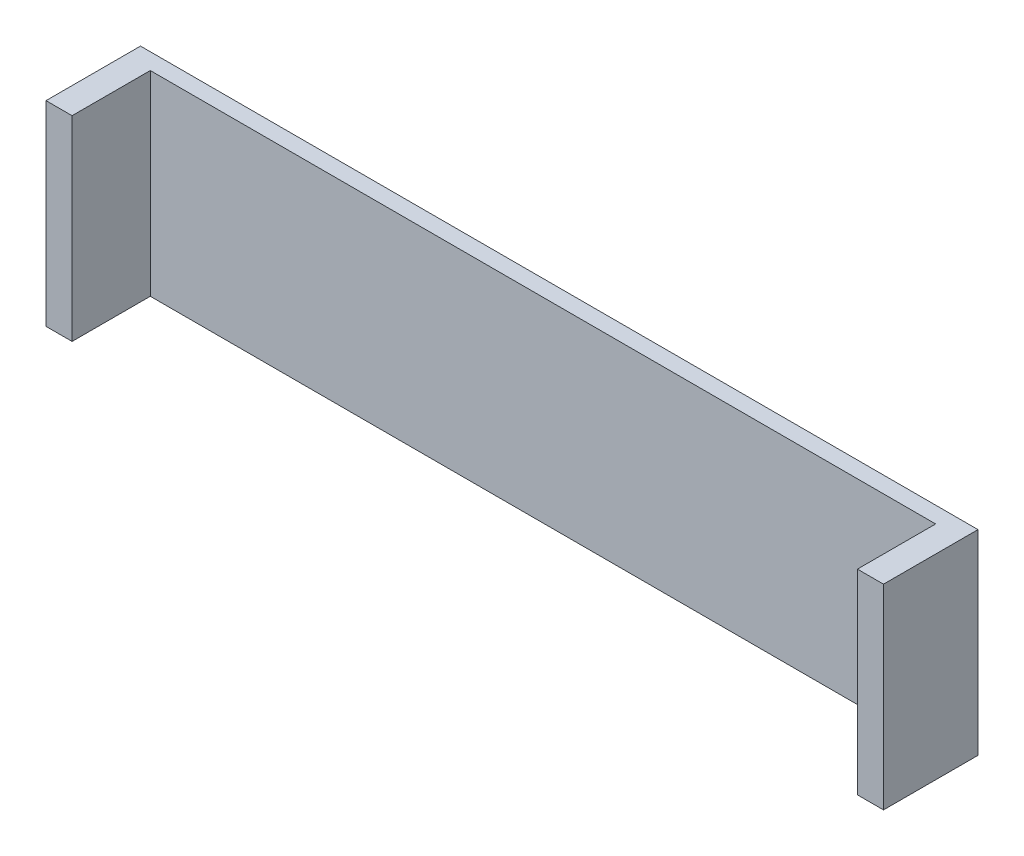
SolidWorks part; units mm, degrees
ref_plane "前视基准面" through (0, 0, 0) normal (0, 0, 1) x (1, 0, 0)
ref_plane "上视基准面" through (0, 0, 0) normal (0, 1, 0) x (1, 0, 0)
ref_plane "右视基准面" through (0, 0, 0) normal (1, 0, 0) x (0, 0, -1)
sketch "草图2" plane through (0, 0, 0) normal (0, 0, 1) x (1, 0, 0)
  line L0 (-15.5168, 35.5479) -> (-15.5168, -24.4521)
  line L1 (-23.5168, -24.4521) -> (233.4832, -24.4521)
  line L2 (-23.5168, -24.4521) -> (-23.5168, 35.5479)
  line L3 (-23.5168, 35.5479) -> (233.4832, 35.5479)
  line L4 (233.4832, -24.4521) -> (233.4832, 35.5479)
  line L5 (225.4832, 35.5479) -> (225.4832, -24.4521)
  dimension "D1" = 60
  dimension "D2" = 257
  dimension "D3" = 8
  dimension "D4" = 8
extrude "凸台-拉伸1" add sketch "草图2" along normal blind 24 contours L3 L2 L1 L0 | L3 L5 L1 L4
sketch "草图3" plane through (0, 0, 0) normal (0, 0, -1) x (-1, 0, 0)
  line L1 (23.5168, -24.4521) -> (-233.4832, -24.4521)
  line L2 (23.5168, -24.4521) -> (23.5168, 35.5479)
  line L3 (23.5168, 35.5479) -> (-233.4832, 35.5479)
  line L4 (-233.4832, -24.4521) -> (-233.4832, 35.5479)
extrude "凸台-拉伸2" add sketch "草图3" along normal blind 5
